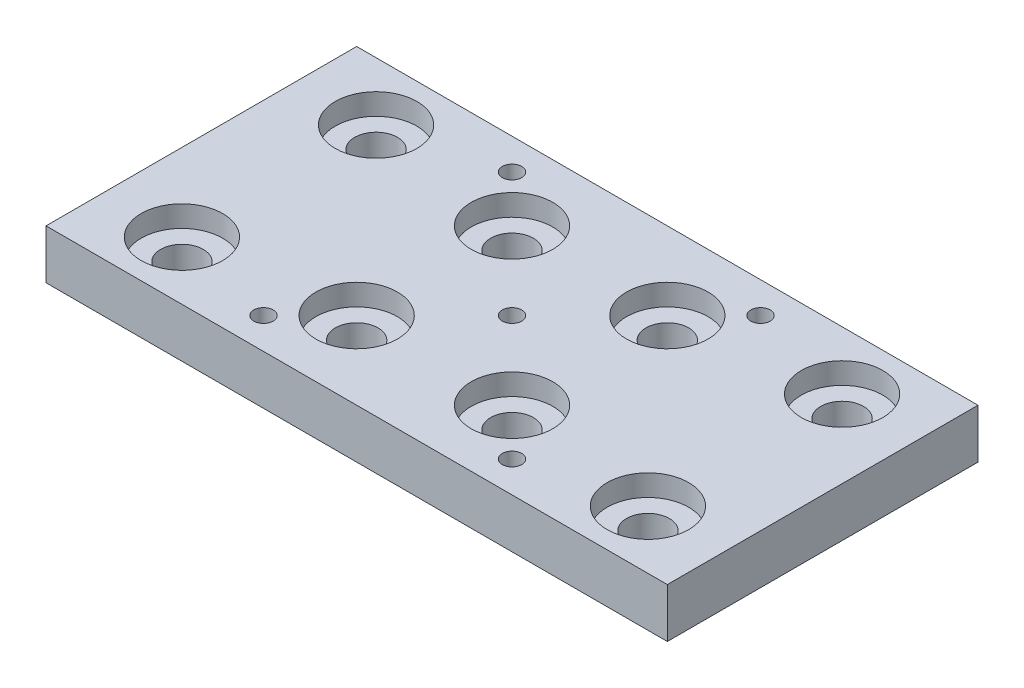
SolidWorks part; units mm, degrees
ref_plane "Front Plane" through (0, 0, 0) normal (0, 0, 1) x (1, 0, 0)
ref_plane "Top Plane" through (0, 0, 0) normal (0, 1, 0) x (1, 0, 0)
ref_plane "Right Plane" through (0, 0, 0) normal (1, 0, 0) x (0, 0, -1)
sketch "Sketch1" plane through (0, 0, 0) normal (0, 1, 0) x (1, 0, 0)
  line L1 (-40, -20) -> (40, -20)
  line L2 (-40, -20) -> (-40, 20)
  line L3 (-40, 20) -> (40, 20)
  line L4 (40, -20) -> (40, 20)
  line L5 (-40, -20) -> (40, 20) construction
  line L6 (-40, 20) -> (40, -20) construction
  point P0 (0, 0)
  dimension "D1" = 40
  dimension "D2" = 80
extrude "Boss-Extrude1" add sketch "Sketch1" along normal blind 6.35
hole_wizard "M3x0.5 Tapped Hole2" positions "Sketch2" profile "Sketch3" tap size "M3x0.5" standard "ANSI Metric" end condition through all
sketch "Sketch2" plane through (0, 6.35, 0) normal (0, 1, 0) x (1, 0, 0)
  line L1 (-16, -16) -> (16, -16) construction
  line L2 (-16, -16) -> (-16, 16) construction
  line L3 (-16, 16) -> (16, 16) construction
  line L4 (16, -16) -> (16, 16) construction
  line L5 (-16, -16) -> (16, 16) construction
  line L6 (-16, 16) -> (16, -16) construction
  point P1 (0, 0)
  point P2 (16, 16)
  point P75 (-16, -16)
  point P76 (-16, 16)
  point P77 (16, -16)
  dimension "D1" = 32
  dimension "D2" = 32
sketch "Sketch3" plane through (0, 6.35, 0) normal (1, 0, 0) x (0, 0, 1)
  line L0 (0, 0) -> (0, 6.35)
  line L1 (0, 6.35) -> (1.25, 6.35)
  line L2 (1.25, 6.35) -> (1.25, 0)
  line L5 (1.25, 0) -> (0, 0)
  line L11 (0, -6.35) -> (0, 107.95) construction
  dimension "Thru Tap Drill Dia." = 2.5
  dimension "Thru Tap Drill Depth" = 6.35
cosmetic thread "Hole Thread1"
cosmetic thread "Hole Thread2"
cosmetic thread "Hole Thread3"
cosmetic thread "Hole Thread4"
cosmetic thread "Hole Thread5"
hole_wizard "CBORE for M5 SBHCS1" positions "Sketch4" profile "Sketch5" counterbore size "M5" standard "ANSI Metric" end condition through all
sketch "Sketch4" plane through (0, 6.35, 0) normal (0, 1, 0) x (1, 0, 0)
  line L0 (0, 0) -> (40, 0) construction
  line L1 (40, -20) -> (40, 20) construction
  line L4 (0, 0) -> (0, 20) construction
  line L5 (40, 20) -> (-40, 20) construction
  point P6 (10, 10)
  point P8 (30, 12.5)
  point P39 (-30, 12.5)
  point P40 (-10, 10)
  point P41 (30, -12.5)
  point P42 (10, -10)
  point P43 (-10, -10)
  point P44 (-30, -12.5)
  dimension "D1" = 10
  dimension "D2" = 10
  dimension "D3" = 30
  dimension "D4" = 12.5
sketch "Sketch5" plane through (10, 6.35, -10) normal (1, 0, 0) x (0, 0, 1)
  line L0 (0, 0) -> (0, 6.35)
  line L1 (0, 6.35) -> (2.75, 6.35)
  line L3 (2.75, 6.35) -> (2.75, 2.75)
  line L4 (2.75, 2.75) -> (5.25, 2.75)
  line L5 (5.25, 2.75) -> (5.25, 0)
  line L7 (5.25, 0) -> (0, 0)
  line L11 (0, -6.35) -> (0, 107.95) construction
  dimension "Thru Hole Dia." = 5.5
  dimension "Thru Hole Depth" = 6.35
  dimension "C'Bore Dia." = 10.5
  dimension "C'Bore Depth" = 2.75
